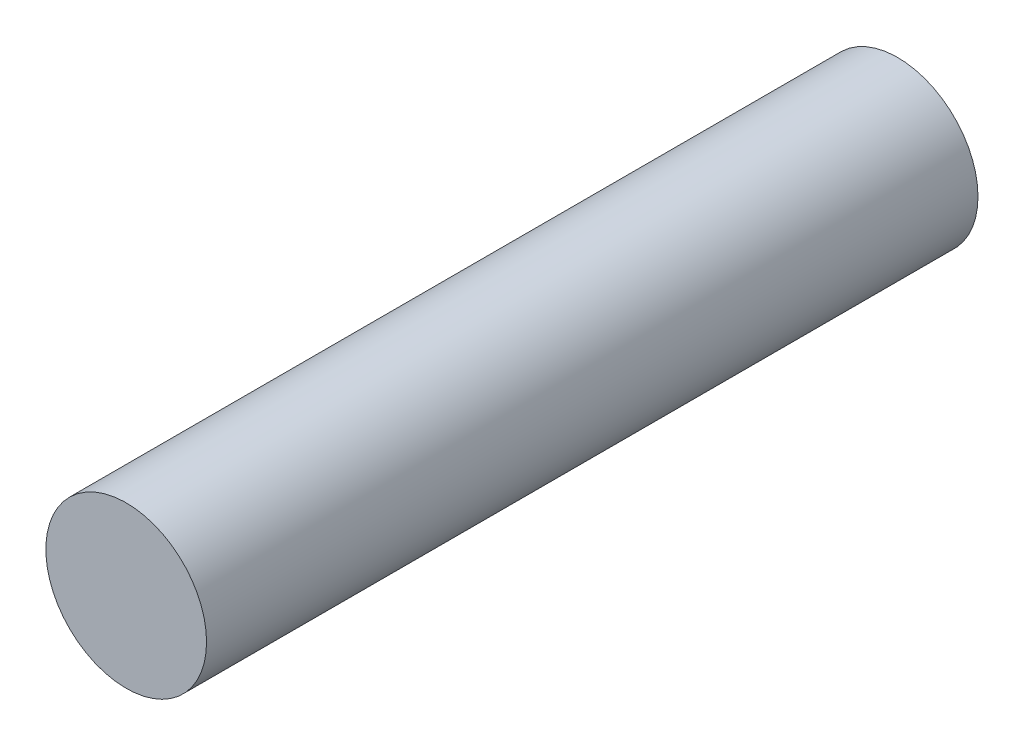
SolidWorks part; units mm, degrees
ref_plane "前视基准面" through (0, 0, 0) normal (0, 0, 1) x (1, 0, 0)
ref_plane "上视基准面" through (0, 0, 0) normal (0, 1, 0) x (1, 0, 0)
ref_plane "右视基准面" through (0, 0, 0) normal (1, 0, 0) x (0, 0, -1)
other "Configuration Table"
sketch "草图1" plane through (0, 0, 0) normal (0, 0, 1) x (1, 0, 0)
  circle A0 centre (0, 0) radius 5
extrude "凸台-拉伸1" add sketch "草图1" along normal blind 48
sketch "草图2" plane through (0, 0, 48) normal (0, 0, 1) x (1, 0, 0)
  line L0 (-4.5826, 2) -> (4.5826, 2)
  circle A0 centre (0, 0) radius 5 construction
  arc A1 (4.5826, 2) -> (-4.5826, 2) centre (0, 0) ccw
